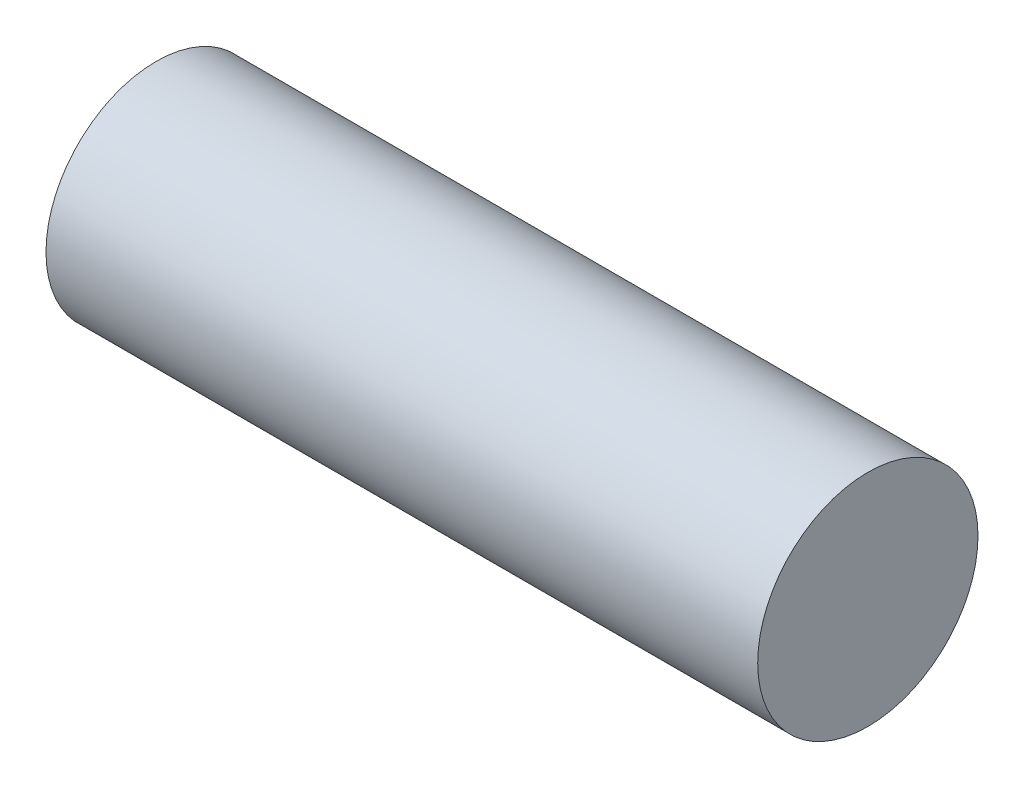
SolidWorks part; units mm, degrees
ref_plane "前视基准面" through (0, 0, 0) normal (0, 0, 1) x (1, 0, 0)
ref_plane "上视基准面" through (0, 0, 0) normal (0, 1, 0) x (1, 0, 0)
ref_plane "右视基准面" through (0, 0, 0) normal (1, 0, 0) x (0, 0, -1)
other "Configuration Table"
sketch "草图1" plane through (0, 0, 0) normal (1, 0, 0) x (0, 0, -1)
  circle A0 centre (0, 0) radius 6.5
extrude "凸台-拉伸1" add sketch "草图1" against normal blind 42
